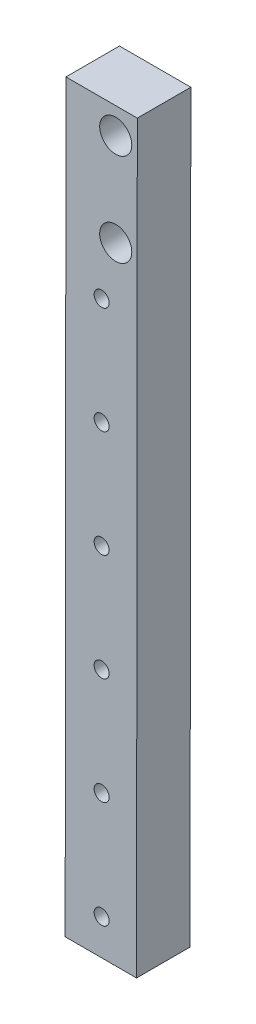
SolidWorks part; units mm, degrees
ref_plane "Front Plane" through (0, 0, 0) normal (0, 0, 1) x (1, 0, 0)
ref_plane "Top Plane" through (0, 0, 0) normal (0, 1, 0) x (1, 0, 0)
ref_plane "Right Plane" through (0, 0, 0) normal (1, 0, 0) x (0, 0, -1)
sketch "Sketch2" plane through (0, 0, 0) normal (0, 0, 1) x (1, 0, 0)
  line L0 (8.763, 64.1131) -> (8.763, 63.8397)
  line L2 (9.7387, 62.864) -> (13.4698, 62.864)
  line L4 (15.0446, 61.2892) -> (15.0446, 60.3748)
  line L6 (13.4698, 58.8) -> (11.075, 58.8)
  line L8 (9.552, 58.8) -> (7.9096, 58.8)
  line L10 (7.9096, 58.8) -> (4.7238, 58.8)
  line L12 (3.2007, 58.8) -> (-3.2007, 58.8)
  line L14 (-4.7238, 58.8) -> (-9.552, 58.8)
  line L16 (-11.075, 58.8) -> (-13.4698, 58.8)
  line L18 (-15.0446, 60.3748) -> (-15.0446, 61.2892)
  line L20 (-13.4698, 62.864) -> (-9.7387, 62.864)
  line L22 (-8.763, 63.8397) -> (-8.763, 64.1131)
  line L24 (-9.1101, 64.9511) -> (-13.8615, 69.7024)
  line L26 (-17.2201, 71.0936) -> (-20.8799, 71.0936)
  line L28 (-24.2385, 69.7024) -> (-29.0766, 64.8643)
  line L30 (-29.337, 64.2357) -> (-29.337, 63.753)
  line L32 (-28.448, 62.864) -> (-24.6302, 62.864)
  line L34 (-23.0554, 61.2892) -> (-23.0554, 60.3748)
  line L36 (-24.6302, 58.8) -> (-27.0238, 58.8)
  line L38 (-28.5453, 58.8) -> (-33.373, 58.8)
  line L40 (-38.1, 63.4712) -> (-38.1, 68.2989)
  line L42 (-38.1, 69.8228) -> (-38.1, 72.2112)
  line L44 (-36.5252, 73.786) -> (-35.6108, 73.786)
  line L46 (-34.036, 72.2112) -> (-34.036, 68.452)
  line L48 (-33.147, 67.563) -> (-32.7207, 67.563)
  line L50 (-31.8885, 67.7998) -> (-27.1976, 72.4907)
  line L52 (-25.8064, 75.8493) -> (-25.8064, 79.8507)
  line L54 (-27.1976, 83.2093) -> (-31.8649, 87.8766)
  line L56 (-32.4935, 88.137) -> (-33.147, 88.137)
  line L58 (-34.036, 87.248) -> (-34.036, 83.4888)
  line L60 (-35.6108, 81.914) -> (-36.5252, 81.914)
  line L62 (-38.1, 83.4888) -> (-38.1, 85.7711)
  line L64 (-38.1, 87.2947) -> (-38.1, 92.1227)
  line L66 (-38.1, 93.6463) -> (-38.1, 100.1537)
  line L68 (-38.1, 101.6773) -> (-38.1, 106.5053)
  line L70 (-38.1, 108.0289) -> (-38.1, 110.3112)
  line L72 (-36.5252, 111.886) -> (-35.6108, 111.886)
  line L74 (-34.036, 110.3112) -> (-34.036, 106.552)
  line L76 (-33.147, 105.663) -> (-32.4935, 105.663)
  line L78 (-31.8649, 105.9234) -> (-27.1976, 110.5907)
  line L80 (-25.8064, 113.9493) -> (-25.8064, 117.9507)
  line L82 (-27.1976, 121.3093) -> (-31.8885, 126.0002)
  line L84 (-32.7207, 126.237) -> (-33.147, 126.237)
  line L86 (-34.036, 125.348) -> (-34.036, 121.5888)
  line L88 (-35.6108, 120.014) -> (-36.5252, 120.014)
  line L90 (-38.1, 121.5888) -> (-38.1, 123.9772)
  line L92 (-38.1, 125.5011) -> (-38.1, 130.3288)
  line L94 (-33.373, 135) -> (-28.5453, 135)
  line L96 (-27.0238, 135) -> (-24.6302, 135)
  line L98 (-23.0554, 133.4252) -> (-23.0554, 132.5108)
  line L100 (-24.6302, 130.936) -> (-28.448, 130.936)
  line L102 (-29.337, 130.047) -> (-29.337, 129.5643)
  line L104 (-29.0766, 128.9357) -> (-24.2385, 124.0976)
  line L106 (-20.8799, 122.7064) -> (-17.2201, 122.7064)
  line L108 (-13.8615, 124.0976) -> (-9.1101, 128.8489)
  line L110 (-8.763, 129.6869) -> (-8.763, 129.9603)
  line L112 (-9.7387, 130.936) -> (-13.4698, 130.936)
  line L114 (-15.0446, 132.5108) -> (-15.0446, 133.4252)
  line L116 (-13.4698, 135) -> (-11.075, 135)
  line L118 (-9.552, 135) -> (-4.7238, 135)
  line L120 (-3.2007, 135) -> (3.2007, 135)
  line L122 (4.7238, 135) -> (9.552, 135)
  line L124 (11.075, 135) -> (13.4698, 135)
  line L126 (15.0446, 133.4252) -> (15.0446, 132.5108)
  line L128 (13.4698, 130.936) -> (9.7387, 130.936)
  line L130 (8.763, 129.9603) -> (8.763, 129.6869)
  line L132 (9.1101, 128.8489) -> (13.8615, 124.0976)
  line L134 (17.2201, 122.7064) -> (20.8799, 122.7064)
  line L136 (24.2385, 124.0976) -> (29.0766, 128.9357)
  line L138 (29.337, 129.5643) -> (29.337, 130.047)
  line L140 (28.448, 130.936) -> (24.6302, 130.936)
  line L142 (23.0554, 132.5108) -> (23.0554, 133.4252)
  line L144 (24.6302, 135) -> (27.0238, 135)
  line L146 (28.5453, 135) -> (33.373, 135)
  line L148 (38.1, 130.3288) -> (38.1, 125.5011)
  line L150 (38.1, 123.9772) -> (38.1, 121.5888)
  line L152 (36.5252, 120.014) -> (35.6108, 120.014)
  line L154 (34.036, 121.5888) -> (34.036, 125.348)
  line L156 (33.147, 126.237) -> (32.7207, 126.237)
  line L158 (31.8885, 126.0002) -> (27.1976, 121.3093)
  line L160 (25.8064, 117.9507) -> (25.8064, 113.9493)
  line L162 (27.1976, 110.5907) -> (31.8649, 105.9234)
  line L164 (32.4935, 105.663) -> (33.147, 105.663)
  line L166 (34.036, 106.552) -> (34.036, 110.3112)
  line L168 (35.6108, 111.886) -> (36.5252, 111.886)
  line L170 (38.1, 110.3112) -> (38.1, 108.0289)
  line L172 (38.1, 106.5053) -> (38.1, 101.6773)
  line L174 (38.1, 100.1537) -> (38.1, 93.6463)
  line L176 (38.1, 92.1227) -> (38.1, 87.2947)
  line L178 (38.1, 85.7711) -> (38.1, 83.4888)
  line L180 (36.5252, 81.914) -> (35.6108, 81.914)
  line L182 (34.036, 83.4888) -> (34.036, 87.248)
  line L184 (33.147, 88.137) -> (32.4935, 88.137)
  line L186 (31.8649, 87.8766) -> (27.1976, 83.2093)
  line L188 (25.8064, 79.8507) -> (25.8064, 75.8493)
  line L190 (27.1976, 72.4907) -> (31.8885, 67.7998)
  line L192 (32.7207, 67.563) -> (33.147, 67.563)
  line L194 (34.036, 68.452) -> (34.036, 72.2112)
  line L196 (35.6108, 73.786) -> (36.5252, 73.786)
  line L198 (38.1, 72.2112) -> (38.1, 69.8228)
  line L200 (38.1, 68.2989) -> (38.1, 63.4712)
  line L202 (33.373, 58.8) -> (28.5453, 58.8)
  line L203 (33.373, 58.8) -> (28.5453, 58.8)
  line L204 (27.0238, 58.8) -> (24.6302, 58.8)
  line L206 (23.0554, 60.3748) -> (23.0554, 61.2892)
  line L208 (24.6302, 62.864) -> (28.448, 62.864)
  line L210 (29.337, 63.753) -> (29.337, 64.2357)
  line L212 (29.0766, 64.8643) -> (24.2385, 69.7024)
  line L214 (20.8799, 71.0936) -> (17.2201, 71.0936)
  line L216 (13.8615, 69.7024) -> (9.1101, 64.9511)
  line L218 (33.373, 58.8) -> (38.1, 58.8)
  line L219 (38.1, -150.0267) -> (38.1, 175) construction
  line L220 (38.1, 58.8) -> (18.1, 58.8)
  line L221 (38.1, 58.8) -> (37.8857, -150.0267)
  line L222 (38.1, -150.0267) -> (7.9096, -150.0267) construction
  line L223 (37.8857, -150.0267) -> (17.8857, -150.0267)
  line L224 (17.8857, -150.0267) -> (18.1, 58.8)
  arc A0 (9.1101, 64.9511) -> (8.763, 64.1131) centre (9.9481, 64.1131) ccw
  arc A2 (8.763, 63.8397) -> (9.7387, 62.864) centre (9.7387, 63.8397) ccw
  arc A4 (15.0446, 61.2892) -> (13.4698, 62.864) centre (13.4698, 61.2892) ccw
  arc A6 (13.4698, 58.8) -> (15.0446, 60.3748) centre (13.4698, 60.3748) ccw
  arc A8 (11.075, 58.8) -> (9.552, 58.8) centre (10.3135, 58.9965) ccw
  arc A10 (4.7238, 58.8) -> (3.2007, 58.8) centre (3.9622, 58.9965) ccw
  arc A12 (-3.2007, 58.8) -> (-4.7238, 58.8) centre (-3.9622, 58.9965) ccw
  arc A14 (-9.552, 58.8) -> (-11.075, 58.8) centre (-10.3135, 58.9965) ccw
  arc A16 (-15.0446, 60.3748) -> (-13.4698, 58.8) centre (-13.4698, 60.3748) ccw
  arc A18 (-13.4698, 62.864) -> (-15.0446, 61.2892) centre (-13.4698, 61.2892) ccw
  arc A20 (-9.7387, 62.864) -> (-8.763, 63.8397) centre (-9.7387, 63.8397) ccw
  arc A22 (-8.763, 64.1131) -> (-9.1101, 64.9511) centre (-9.9481, 64.1131) ccw
  arc A24 (-13.8615, 69.7024) -> (-17.2201, 71.0936) centre (-17.2201, 66.3438) ccw
  arc A26 (-20.8799, 71.0936) -> (-24.2385, 69.7024) centre (-20.8799, 66.3438) ccw
  arc A28 (-29.0766, 64.8643) -> (-29.337, 64.2357) centre (-28.448, 64.2357) ccw
  arc A30 (-29.337, 63.753) -> (-28.448, 62.864) centre (-28.448, 63.753) ccw
  arc A32 (-23.0554, 61.2892) -> (-24.6302, 62.864) centre (-24.6302, 61.2892) ccw
  arc A34 (-24.6302, 58.8) -> (-23.0554, 60.3748) centre (-24.6302, 60.3748) ccw
  arc A36 (-27.0238, 58.8) -> (-28.5453, 58.8) centre (-27.7845, 58.9965) ccw
  arc A38 (-33.373, 58.8) -> (-34.8455, 58.8) centre (-34.1092, 58.9965) ccw
  arc A40 (-37.1826, 59.8139) -> (-34.8455, 58.8) centre (-34.8566, 61.975) ccw
  arc A42 (-38.1, 61.9473) -> (-37.1826, 59.8139) centre (-34.9266, 62.0479) ccw
  arc A44 (-38.1, 61.9473) -> (-38.1, 63.4712) centre (-38.0824, 62.7093) ccw
  arc A46 (-38.1, 68.2989) -> (-38.1, 69.8228) centre (-38.0824, 69.0608) ccw
  arc A48 (-36.5252, 73.786) -> (-38.1, 72.2112) centre (-36.5252, 72.2112) ccw
  arc A50 (-34.036, 72.2112) -> (-35.6108, 73.786) centre (-35.6108, 72.2112) ccw
  arc A52 (-34.036, 68.452) -> (-33.147, 67.563) centre (-33.147, 68.452) ccw
  arc A54 (-32.7207, 67.563) -> (-31.8885, 67.7998) centre (-32.5172, 68.4284) ccw
  arc A56 (-27.1976, 72.4907) -> (-25.8064, 75.8493) centre (-30.5562, 75.8493) ccw
  arc A58 (-25.8064, 79.8507) -> (-27.1976, 83.2093) centre (-30.5562, 79.8507) ccw
  arc A60 (-31.8649, 87.8766) -> (-32.4935, 88.137) centre (-32.4935, 87.248) ccw
  arc A62 (-33.147, 88.137) -> (-34.036, 87.248) centre (-33.147, 87.248) ccw
  arc A64 (-35.6108, 81.914) -> (-34.036, 83.4888) centre (-35.6108, 83.4888) ccw
  arc A66 (-38.1, 83.4888) -> (-36.5252, 81.914) centre (-36.5252, 83.4888) ccw
  arc A68 (-38.1, 85.7711) -> (-38.1, 87.2947) centre (-38.0824, 86.5329) ccw
  arc A70 (-38.1, 92.1227) -> (-38.1, 93.6463) centre (-38.0824, 92.8845) ccw
  arc A72 (-38.1, 100.1537) -> (-38.1, 101.6773) centre (-38.0824, 100.9155) ccw
  arc A74 (-38.1, 106.5053) -> (-38.1, 108.0289) centre (-38.0824, 107.2671) ccw
  arc A76 (-36.5252, 111.886) -> (-38.1, 110.3112) centre (-36.5252, 110.3112) ccw
  arc A78 (-34.036, 110.3112) -> (-35.6108, 111.886) centre (-35.6108, 110.3112) ccw
  arc A80 (-34.036, 106.552) -> (-33.147, 105.663) centre (-33.147, 106.552) ccw
  arc A82 (-32.4935, 105.663) -> (-31.8649, 105.9234) centre (-32.4935, 106.552) ccw
  arc A84 (-27.1976, 110.5907) -> (-25.8064, 113.9493) centre (-30.5562, 113.9493) ccw
  arc A86 (-25.8064, 117.9507) -> (-27.1976, 121.3093) centre (-30.5562, 117.9507) ccw
  arc A88 (-31.8885, 126.0002) -> (-32.7207, 126.237) centre (-32.5172, 125.3716) ccw
  arc A90 (-33.147, 126.237) -> (-34.036, 125.348) centre (-33.147, 125.348) ccw
  arc A92 (-35.6108, 120.014) -> (-34.036, 121.5888) centre (-35.6108, 121.5888) ccw
  arc A94 (-38.1, 121.5888) -> (-36.5252, 120.014) centre (-36.5252, 121.5888) ccw
  arc A96 (-38.1, 123.9772) -> (-38.1, 125.5011) centre (-38.0824, 124.7392) ccw
  arc A98 (-38.1, 130.3288) -> (-38.1, 131.8527) centre (-38.0824, 131.0907) ccw
  arc A100 (-37.1826, 133.9861) -> (-38.1, 131.8527) centre (-34.9266, 131.7521) ccw
  arc A102 (-34.8455, 135) -> (-37.1826, 133.9861) centre (-34.8566, 131.825) ccw
  arc A104 (-34.8455, 135) -> (-33.373, 135) centre (-34.1092, 134.8035) ccw
  arc A106 (-28.5453, 135) -> (-27.0238, 135) centre (-27.7845, 134.8035) ccw
  arc A108 (-23.0554, 133.4252) -> (-24.6302, 135) centre (-24.6302, 133.4252) ccw
  arc A110 (-24.6302, 130.936) -> (-23.0554, 132.5108) centre (-24.6302, 132.5108) ccw
  arc A112 (-28.448, 130.936) -> (-29.337, 130.047) centre (-28.448, 130.047) ccw
  arc A114 (-29.337, 129.5643) -> (-29.0766, 128.9357) centre (-28.448, 129.5643) ccw
  arc A116 (-24.2385, 124.0976) -> (-20.8799, 122.7064) centre (-20.8799, 127.4562) ccw
  arc A118 (-17.2201, 122.7064) -> (-13.8615, 124.0976) centre (-17.2201, 127.4562) ccw
  arc A120 (-9.1101, 128.8489) -> (-8.763, 129.6869) centre (-9.9481, 129.6869) ccw
  arc A122 (-8.763, 129.9603) -> (-9.7387, 130.936) centre (-9.7387, 129.9603) ccw
  arc A124 (-15.0446, 132.5108) -> (-13.4698, 130.936) centre (-13.4698, 132.5108) ccw
  arc A126 (-13.4698, 135) -> (-15.0446, 133.4252) centre (-13.4698, 133.4252) ccw
  arc A128 (-11.075, 135) -> (-9.552, 135) centre (-10.3135, 134.8035) ccw
  arc A130 (-4.7238, 135) -> (-3.2007, 135) centre (-3.9622, 134.8035) ccw
  arc A132 (3.2007, 135) -> (4.7238, 135) centre (3.9622, 134.8035) ccw
  arc A134 (9.552, 135) -> (11.075, 135) centre (10.3135, 134.8035) ccw
  arc A136 (15.0446, 133.4252) -> (13.4698, 135) centre (13.4698, 133.4252) ccw
  arc A138 (13.4698, 130.936) -> (15.0446, 132.5108) centre (13.4698, 132.5108) ccw
  arc A140 (9.7387, 130.936) -> (8.763, 129.9603) centre (9.7387, 129.9603) ccw
  arc A142 (8.763, 129.6869) -> (9.1101, 128.8489) centre (9.9481, 129.6869) ccw
  arc A144 (13.8615, 124.0976) -> (17.2201, 122.7064) centre (17.2201, 127.4562) ccw
  arc A146 (20.8799, 122.7064) -> (24.2385, 124.0976) centre (20.8799, 127.4562) ccw
  arc A148 (29.0766, 128.9357) -> (29.337, 129.5643) centre (28.448, 129.5643) ccw
  arc A150 (29.337, 130.047) -> (28.448, 130.936) centre (28.448, 130.047) ccw
  arc A152 (23.0554, 132.5108) -> (24.6302, 130.936) centre (24.6302, 132.5108) ccw
  arc A154 (24.6302, 135) -> (23.0554, 133.4252) centre (24.6302, 133.4252) ccw
  arc A156 (27.0238, 135) -> (28.5453, 135) centre (27.7845, 134.8035) ccw
  arc A158 (33.373, 135) -> (34.8455, 135) centre (34.1092, 134.8035) ccw
  arc A160 (37.1826, 133.9861) -> (34.8455, 135) centre (34.8566, 131.825) ccw
  arc A162 (38.1, 131.8527) -> (37.1826, 133.9861) centre (34.9266, 131.7521) ccw
  arc A164 (38.1, 131.8527) -> (38.1, 130.3288) centre (38.0824, 131.0907) ccw
  arc A166 (38.1, 125.5011) -> (38.1, 123.9772) centre (38.0824, 124.7392) ccw
  arc A168 (36.5252, 120.014) -> (38.1, 121.5888) centre (36.5252, 121.5888) ccw
  arc A170 (34.036, 121.5888) -> (35.6108, 120.014) centre (35.6108, 121.5888) ccw
  arc A172 (34.036, 125.348) -> (33.147, 126.237) centre (33.147, 125.348) ccw
  arc A174 (32.7207, 126.237) -> (31.8885, 126.0002) centre (32.5172, 125.3716) ccw
  arc A176 (27.1976, 121.3093) -> (25.8064, 117.9507) centre (30.5562, 117.9507) ccw
  arc A178 (25.8064, 113.9493) -> (27.1976, 110.5907) centre (30.5562, 113.9493) ccw
  arc A180 (31.8649, 105.9234) -> (32.4935, 105.663) centre (32.4935, 106.552) ccw
  arc A182 (33.147, 105.663) -> (34.036, 106.552) centre (33.147, 106.552) ccw
  arc A184 (35.6108, 111.886) -> (34.036, 110.3112) centre (35.6108, 110.3112) ccw
  arc A186 (38.1, 110.3112) -> (36.5252, 111.886) centre (36.5252, 110.3112) ccw
  arc A188 (38.1, 108.0289) -> (38.1, 106.5053) centre (38.0824, 107.2671) ccw
  arc A190 (38.1, 101.6773) -> (38.1, 100.1537) centre (38.0824, 100.9155) ccw
  arc A192 (38.1, 93.6463) -> (38.1, 92.1227) centre (38.0824, 92.8845) ccw
  arc A194 (38.1, 87.2947) -> (38.1, 85.7711) centre (38.0824, 86.5329) ccw
  arc A196 (36.5252, 81.914) -> (38.1, 83.4888) centre (36.5252, 83.4888) ccw
  arc A198 (34.036, 83.4888) -> (35.6108, 81.914) centre (35.6108, 83.4888) ccw
  arc A200 (34.036, 87.248) -> (33.147, 88.137) centre (33.147, 87.248) ccw
  arc A202 (32.4935, 88.137) -> (31.8649, 87.8766) centre (32.4935, 87.248) ccw
  arc A204 (27.1976, 83.2093) -> (25.8064, 79.8507) centre (30.5562, 79.8507) ccw
  arc A206 (25.8064, 75.8493) -> (27.1976, 72.4907) centre (30.5562, 75.8493) ccw
  arc A208 (31.8885, 67.7998) -> (32.7207, 67.563) centre (32.5172, 68.4284) ccw
  arc A210 (33.147, 67.563) -> (34.036, 68.452) centre (33.147, 68.452) ccw
  arc A212 (35.6108, 73.786) -> (34.036, 72.2112) centre (35.6108, 72.2112) ccw
  arc A214 (38.1, 72.2112) -> (36.5252, 73.786) centre (36.5252, 72.2112) ccw
  arc A216 (38.1, 69.8228) -> (38.1, 68.2989) centre (38.0824, 69.0608) ccw
  arc A218 (38.1, 63.4712) -> (38.1, 61.9473) centre (38.0824, 62.7093) ccw
  arc A220 (37.1826, 59.8139) -> (38.1, 61.9473) centre (34.9266, 62.0479) ccw
  arc A222 (34.8455, 58.8) -> (37.1826, 59.8139) centre (34.8566, 61.975) ccw
  arc A224 (34.8455, 58.8) -> (33.373, 58.8) centre (34.1092, 58.9965) ccw
  arc A226 (28.5453, 58.8) -> (27.0238, 58.8) centre (27.7845, 58.9965) ccw
  arc A228 (23.0554, 60.3748) -> (24.6302, 58.8) centre (24.6302, 60.3748) ccw
  arc A230 (24.6302, 62.864) -> (23.0554, 61.2892) centre (24.6302, 61.2892) ccw
  arc A232 (28.448, 62.864) -> (29.337, 63.753) centre (28.448, 63.753) ccw
  arc A234 (29.337, 64.2357) -> (29.0766, 64.8643) centre (28.448, 64.2357) ccw
  arc A236 (24.2385, 69.7024) -> (20.8799, 71.0936) centre (20.8799, 66.3438) ccw
  arc A238 (17.2201, 71.0936) -> (13.8615, 69.7024) centre (17.2201, 66.3438) ccw
  circle M1 centre (28.1, -140.0267) radius 2.1
  circle M2 centre (28.1, -110.0267) radius 2.1
  circle M3 centre (28.1, -80.0267) radius 2.1
  circle M4 centre (28.1, -50.0267) radius 2.1
  circle M5 centre (28.1, -20.0267) radius 2.1
  circle M6 centre (28.1, 9.9733) radius 2.1
  line M11 (7.9096, -150.0267) -> (38.1, -150.0267)
  circle M17 centre (32.05, 25.5) radius 4.5
  circle M18 centre (32.05, 51.5) radius 4.5
extrude "Boss-Extrude1" add sketch "Sketch2" along normal blind 15 contours L224 L221 L218 L203 L220 M11 M2 M4 M6 M17 M18 M5 M3 M1
